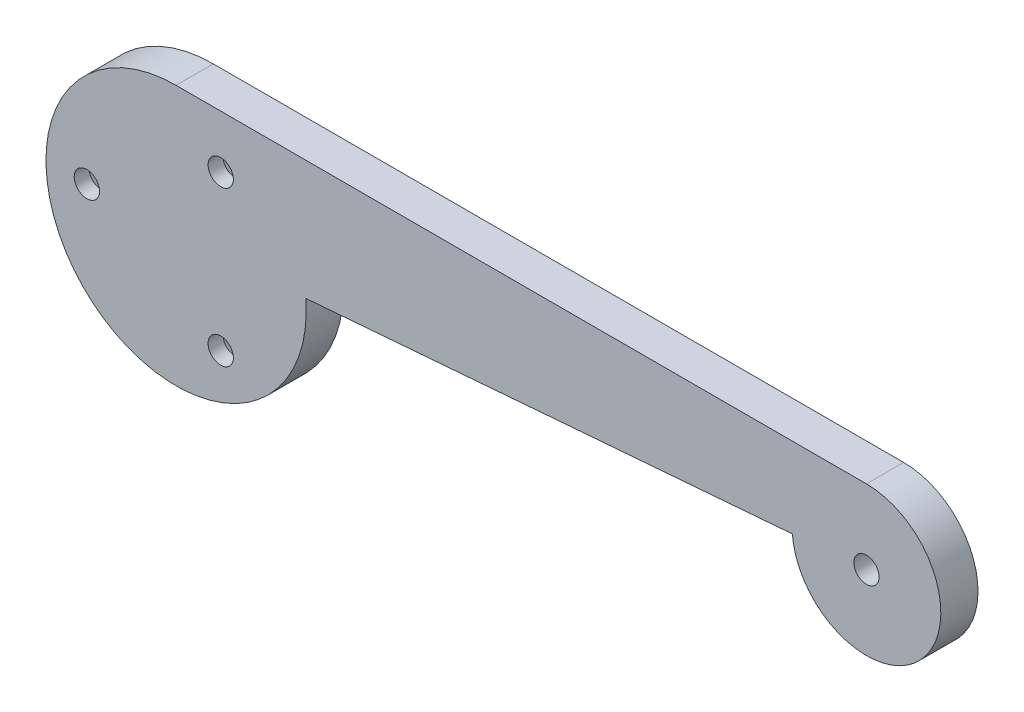
SolidWorks part; units mm, degrees
ref_plane "Front Plane" through (0, 0, 0) normal (0, 0, 1) x (1, 0, 0)
ref_plane "Top Plane" through (0, 0, 0) normal (0, 1, 0) x (1, 0, 0)
ref_plane "Right Plane" through (0, 0, 0) normal (1, 0, 0) x (0, 0, -1)
sketch "Sketch1" plane through (0, 0, 0) normal (0, 0, 1) x (1, 0, 0)
  line L0 (0, 0) -> (90, 0) construction
  line L1 (0, 17.5) -> (92.8257, 17.5)
  line L2 (17.4432, 1.4093) -> (82.8582, 6.6947)
  line L3 (82.8582, 6.6947) -> (82.6496, 9.2766) construction
  line L4 (17.4432, 1.4093) -> (16.6278, 11.5008) construction
  arc A0 (0, 17.5) -> (17.4432, 1.4093) centre (0, 0) ccw
  arc A1 (92.8257, 17.5) -> (82.8582, 6.6947) centre (92.8257, 7.5) cw
  dimension "D1" = 17.5
  dimension "D3" = 10
  dimension "D2" = 90
  dimension "D4" = 90
  dimension "D5" = 90
extrude "Boss-Extrude1" add sketch "Sketch1" along normal blind 5
hole_wizard "M3 Clearance Hole1" positions "Sketch6" profile "Sketch7" hole size "M3" standard "ISO" end condition through all
sketch "Sketch6" plane through (0, 0, 5) normal (0, 0, 1) x (1, 0, 0)
  point P0 (-12, 0)
  dimension "D1" = 12
sketch "Sketch7" plane through (-12, 0, 5) normal (1, 0, 0) x (0, -1, 0)
  line L0 (0, 0) -> (0, 5)
  line L1 (0, 5) -> (1.7, 5)
  line L2 (1.7, 5) -> (1.7, 0)
  line L5 (1.7, 0) -> (0, 0)
  line L11 (0, -6.35) -> (0, 107.95) construction
  dimension "Thru Hole Dia." = 3.4
  dimension "Thru Hole Depth" = 5
sketch "Sketch8" plane through (0, 0, 0) normal (0, 0, 1) x (1, 0, 0)
  line L1 (-10.3834, 2.8) -> (-13.6166, 2.8)
  line L2 (-13.6166, 2.8) -> (-15.2332, 0)
  line L3 (-15.2332, 0) -> (-13.6166, -2.8)
  line L4 (-13.6166, -2.8) -> (-10.3834, -2.8)
  line L5 (-10.3834, -2.8) -> (-8.7668, 0)
  line L6 (-8.7668, 0) -> (-10.3834, 2.8)
  circle A0 centre (-12, 0) radius 2.8 construction
  dimension "D1" = 5.6
extrude "Cut-Extrude1" cut sketch "Sketch8" along normal blind 3
pattern_circular "CirPattern1" count 3 over 360 about axis through (0, 0, 0) along (0, 0, 1) of "Cut-Extrude1", "M3 Clearance Hole1"
hole_wizard "M3 Clearance Hole2" positions "Sketch10" profile "Sketch11" hole size "M3" standard "ISO" end condition through all
sketch "Sketch10" plane through (0, 0, 5) normal (0, 0, 1) x (1, 0, 0)
  point P11 (92.8257, 7.5)
sketch "Sketch11" plane through (92.8257, 7.5, 5) normal (1, 0, 0) x (0, -1, 0)
  line L0 (0, 0) -> (0, 5)
  line L1 (0, 5) -> (1.7, 5)
  line L2 (1.7, 5) -> (1.7, 0)
  line L5 (1.7, 0) -> (0, 0)
  line L11 (0, -6.35) -> (0, 107.95) construction
  dimension "Thru Hole Dia." = 3.4
  dimension "Thru Hole Depth" = 5
